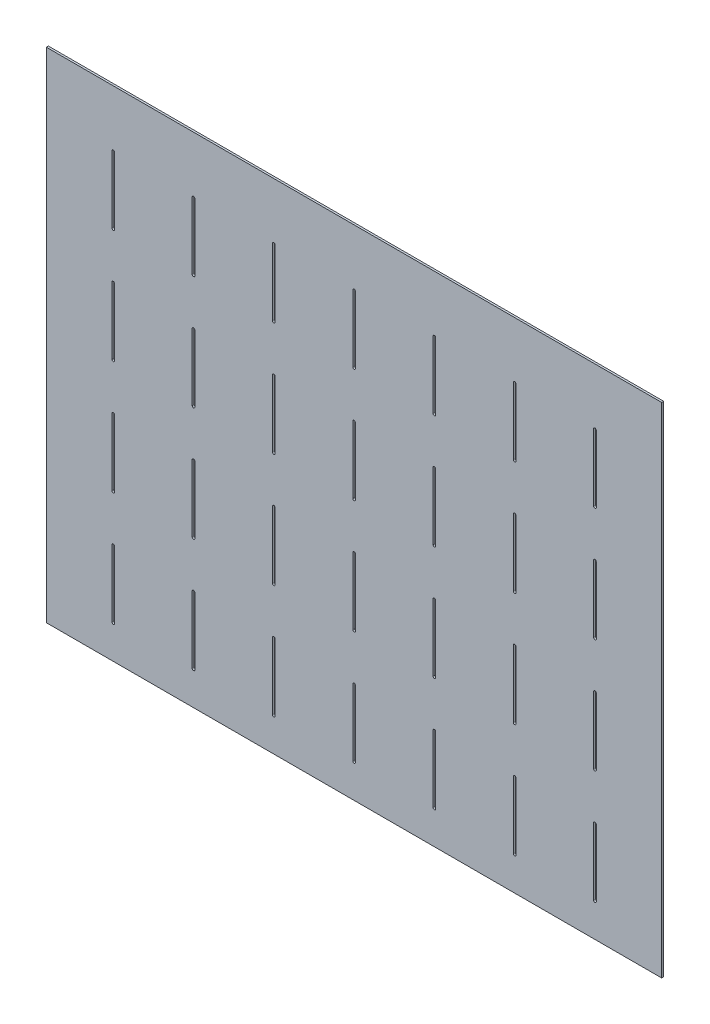
SolidWorks part; units mm, degrees
ref_plane "Front" through (0, 0, 0) normal (0, 0, 1) x (1, 0, 0)
ref_plane "Top" through (0, 0, 0) normal (0, 1, 0) x (1, 0, 0)
ref_plane "Right" through (0, 0, 0) normal (1, 0, 0) x (0, 0, -1)
sketch "Эскиз1" plane through (0, 0, 0) normal (0, 0, 1) x (1, 0, 0)
  line L0 (-40, -3) -> (879.7251, -3)
  line L1 (-40, -3) -> (-40, 742)
  line L2 (879.7251, -3) -> (879.7251, 742)
  line L3 (-40, 742) -> (879.7251, 742)
  dimension "D1" = 745
extrude "Бобышка-Вытянуть1" add sketch "Эскиз1" along normal blind 3
sketch "Эскиз3" plane through (0, 0, 0) normal (0, 0, -1) x (-1, 0, 0)
  line L0 (-60, -933.1644) -> (-60, 49066.8356) construction
  line L1 (-60, 47) -> (-60, 147) construction
  line L2 (-62, 47) -> (-62, 147)
  line L3 (-58, 47) -> (-58, 147)
  line L4 (-180, 47) -> (-180, 147) construction
  line L5 (40, -3) -> (-879.7251, -3) construction
  line L6 (-182, 47) -> (-182, 147)
  line L7 (-178, 47) -> (-178, 147)
  line L8 (-300, 47) -> (-300, 147) construction
  line L9 (-302, 47) -> (-302, 147)
  line L10 (-298, 47) -> (-298, 147)
  line L11 (-420, 47) -> (-420, 147) construction
  line L12 (-422, 47) -> (-422, 147)
  line L13 (-418, 47) -> (-418, 147)
  line L14 (-540, 47) -> (-540, 147) construction
  line L15 (-542, 47) -> (-542, 147)
  line L16 (-538, 47) -> (-538, 147)
  line L17 (-660, 47) -> (-660, 147) construction
  line L18 (-662, 47) -> (-662, 147)
  line L19 (-658, 47) -> (-658, 147)
  line L20 (-780, 47) -> (-780, 147) construction
  line L21 (-782, 47) -> (-782, 147)
  line L22 (-778, 47) -> (-778, 147)
  line L23 (-180, 217) -> (-180, 317) construction
  line L24 (-182, 217) -> (-182, 317)
  line L25 (-178, 217) -> (-178, 317)
  line L26 (-300, 217) -> (-300, 317) construction
  line L27 (-302, 217) -> (-302, 317)
  line L28 (-298, 217) -> (-298, 317)
  line L29 (-420, 217) -> (-420, 317) construction
  line L30 (-422, 217) -> (-422, 317)
  line L31 (-418, 217) -> (-418, 317)
  line L32 (-540, 217) -> (-540, 317) construction
  line L33 (-542, 217) -> (-542, 317)
  line L34 (-538, 217) -> (-538, 317)
  line L35 (-660, 217) -> (-660, 317) construction
  line L36 (-662, 217) -> (-662, 317)
  line L37 (-658, 217) -> (-658, 317)
  line L38 (-780, 217) -> (-780, 317) construction
  line L39 (-782, 217) -> (-782, 317)
  line L40 (-778, 217) -> (-778, 317)
  line L41 (-180, 387) -> (-180, 487) construction
  line L42 (-182, 387) -> (-182, 487)
  line L43 (-178, 387) -> (-178, 487)
  line L44 (-300, 387) -> (-300, 487) construction
  line L45 (-302, 387) -> (-302, 487)
  line L46 (-298, 387) -> (-298, 487)
  line L47 (-420, 387) -> (-420, 487) construction
  line L48 (-422, 387) -> (-422, 487)
  line L49 (-418, 387) -> (-418, 487)
  line L50 (-540, 387) -> (-540, 487) construction
  line L51 (-542, 387) -> (-542, 487)
  line L52 (-538, 387) -> (-538, 487)
  line L53 (-660, 387) -> (-660, 487) construction
  line L54 (-662, 387) -> (-662, 487)
  line L55 (-658, 387) -> (-658, 487)
  line L56 (-780, 387) -> (-780, 487) construction
  line L57 (-782, 387) -> (-782, 487)
  line L58 (-778, 387) -> (-778, 487)
  line L59 (-180, 557) -> (-180, 657) construction
  line L60 (-182, 557) -> (-182, 657)
  line L61 (-178, 557) -> (-178, 657)
  line L62 (-300, 557) -> (-300, 657) construction
  line L63 (-302, 557) -> (-302, 657)
  line L64 (-298, 557) -> (-298, 657)
  line L65 (-420, 557) -> (-420, 657) construction
  line L66 (-422, 557) -> (-422, 657)
  line L67 (-418, 557) -> (-418, 657)
  line L68 (-540, 557) -> (-540, 657) construction
  line L69 (-542, 557) -> (-542, 657)
  line L70 (-538, 557) -> (-538, 657)
  line L71 (-660, 557) -> (-660, 657) construction
  line L72 (-662, 557) -> (-662, 657)
  line L73 (-658, 557) -> (-658, 657)
  line L74 (-780, 557) -> (-780, 657) construction
  line L75 (-782, 557) -> (-782, 657)
  line L76 (-778, 557) -> (-778, 657)
  line L77 (-60, 217) -> (-60, 317) construction
  line L78 (-62, 217) -> (-62, 317)
  line L79 (-58, 217) -> (-58, 317)
  line L80 (-60, 387) -> (-60, 487) construction
  line L81 (-62, 387) -> (-62, 487)
  line L82 (-58, 387) -> (-58, 487)
  line L83 (-60, 557) -> (-60, 657) construction
  line L84 (-62, 557) -> (-62, 657)
  line L85 (-58, 557) -> (-58, 657)
  arc A0 (-62, 47) -> (-58, 47) centre (-60, 47) ccw
  arc A1 (-58, 147) -> (-62, 147) centre (-60, 147) ccw
  arc A2 (-182, 47) -> (-178, 47) centre (-180, 47) ccw
  arc A3 (-178, 147) -> (-182, 147) centre (-180, 147) ccw
  arc A4 (-302, 47) -> (-298, 47) centre (-300, 47) ccw
  arc A5 (-298, 147) -> (-302, 147) centre (-300, 147) ccw
  arc A6 (-422, 47) -> (-418, 47) centre (-420, 47) ccw
  arc A7 (-418, 147) -> (-422, 147) centre (-420, 147) ccw
  arc A8 (-542, 47) -> (-538, 47) centre (-540, 47) ccw
  arc A9 (-538, 147) -> (-542, 147) centre (-540, 147) ccw
  arc A10 (-662, 47) -> (-658, 47) centre (-660, 47) ccw
  arc A11 (-658, 147) -> (-662, 147) centre (-660, 147) ccw
  arc A12 (-782, 47) -> (-778, 47) centre (-780, 47) ccw
  arc A13 (-778, 147) -> (-782, 147) centre (-780, 147) ccw
  arc A14 (-182, 217) -> (-178, 217) centre (-180, 217) ccw
  arc A15 (-178, 317) -> (-182, 317) centre (-180, 317) ccw
  arc A16 (-302, 217) -> (-298, 217) centre (-300, 217) ccw
  arc A17 (-298, 317) -> (-302, 317) centre (-300, 317) ccw
  arc A18 (-422, 217) -> (-418, 217) centre (-420, 217) ccw
  arc A19 (-418, 317) -> (-422, 317) centre (-420, 317) ccw
  arc A20 (-542, 217) -> (-538, 217) centre (-540, 217) ccw
  arc A21 (-538, 317) -> (-542, 317) centre (-540, 317) ccw
  arc A22 (-662, 217) -> (-658, 217) centre (-660, 217) ccw
  arc A23 (-658, 317) -> (-662, 317) centre (-660, 317) ccw
  arc A24 (-782, 217) -> (-778, 217) centre (-780, 217) ccw
  arc A25 (-778, 317) -> (-782, 317) centre (-780, 317) ccw
  arc A26 (-182, 387) -> (-178, 387) centre (-180, 387) ccw
  arc A27 (-178, 487) -> (-182, 487) centre (-180, 487) ccw
  arc A28 (-302, 387) -> (-298, 387) centre (-300, 387) ccw
  arc A29 (-298, 487) -> (-302, 487) centre (-300, 487) ccw
  arc A30 (-422, 387) -> (-418, 387) centre (-420, 387) ccw
  arc A31 (-418, 487) -> (-422, 487) centre (-420, 487) ccw
  arc A32 (-542, 387) -> (-538, 387) centre (-540, 387) ccw
  arc A33 (-538, 487) -> (-542, 487) centre (-540, 487) ccw
  arc A34 (-662, 387) -> (-658, 387) centre (-660, 387) ccw
  arc A35 (-658, 487) -> (-662, 487) centre (-660, 487) ccw
  arc A36 (-782, 387) -> (-778, 387) centre (-780, 387) ccw
  arc A37 (-778, 487) -> (-782, 487) centre (-780, 487) ccw
  arc A38 (-182, 557) -> (-178, 557) centre (-180, 557) ccw
  arc A39 (-178, 657) -> (-182, 657) centre (-180, 657) ccw
  arc A40 (-302, 557) -> (-298, 557) centre (-300, 557) ccw
  arc A41 (-298, 657) -> (-302, 657) centre (-300, 657) ccw
  arc A42 (-422, 557) -> (-418, 557) centre (-420, 557) ccw
  arc A43 (-418, 657) -> (-422, 657) centre (-420, 657) ccw
  arc A44 (-542, 557) -> (-538, 557) centre (-540, 557) ccw
  arc A45 (-538, 657) -> (-542, 657) centre (-540, 657) ccw
  arc A46 (-662, 557) -> (-658, 557) centre (-660, 557) ccw
  arc A47 (-658, 657) -> (-662, 657) centre (-660, 657) ccw
  arc A48 (-782, 557) -> (-778, 557) centre (-780, 557) ccw
  arc A49 (-778, 657) -> (-782, 657) centre (-780, 657) ccw
  arc A50 (-62, 217) -> (-58, 217) centre (-60, 217) ccw
  arc A51 (-58, 317) -> (-62, 317) centre (-60, 317) ccw
  arc A52 (-62, 387) -> (-58, 387) centre (-60, 387) ccw
  arc A53 (-58, 487) -> (-62, 487) centre (-60, 487) ccw
  arc A54 (-62, 557) -> (-58, 557) centre (-60, 557) ccw
  arc A55 (-58, 657) -> (-62, 657) centre (-60, 657) ccw
  point P5 (-60, 97)
  point P16 (-180, 97)
  point P23 (-300, 97)
  point P30 (-420, 97)
  point P37 (-540, 97)
  point P44 (-660, 97)
  point P51 (-780, 97)
  point P58 (-180, 267)
  point P65 (-300, 267)
  point P72 (-420, 267)
  point P79 (-540, 267)
  point P86 (-660, 267)
  point P93 (-780, 267)
  point P100 (-180, 437)
  point P107 (-300, 437)
  point P114 (-420, 437)
  point P121 (-540, 437)
  point P128 (-660, 437)
  point P135 (-780, 437)
  point P142 (-180, 607)
  point P149 (-300, 607)
  point P156 (-420, 607)
  point P163 (-540, 607)
  point P170 (-660, 607)
  point P177 (-780, 607)
  point P184 (-60, 267)
  point P191 (-60, 437)
  point P198 (-60, 607)
  dimension "D3" = 2
  dimension "D1" = 60
  dimension "D2" = 100
  dimension "D4" = 100
  dimension "D5" = 7
  dimension "D6" = 4
extrude "Вырез-Вытянуть1" cut sketch "Эскиз3" against normal blind 3
